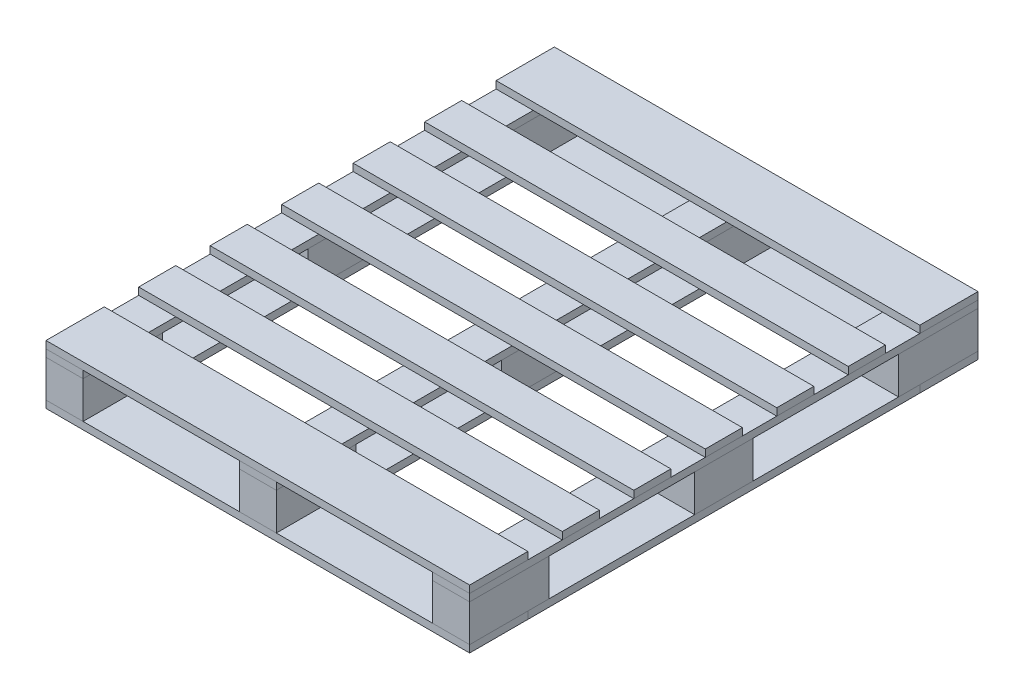
SolidWorks part; units mm, degrees
ref_plane "Front Plane" through (0, 0, 0) normal (0, 0, 1) x (1, 0, 0)
ref_plane "Top Plane" through (0, 0, 0) normal (0, 1, 0) x (1, 0, 0)
ref_plane "Right Plane" through (0, 0, 0) normal (1, 0, 0) x (0, 0, -1)
sketch "Sketch1" plane through (0, 0, 0) normal (0, 0, 1) x (1, 0, 0)
  line L0 (-508, 0) -> (508, 0) construction
  line L5 (-508, 70.612) -> (-508, -70.612) construction
  line L6 (508, 70.612) -> (508, -70.612) construction
  line L11 (-508, -70.612) -> (508, -70.612) construction
  line L12 (-508, 70.612) -> (508, 70.612) construction
  line L13 (-419.1, 70.612) -> (-419.1, -70.612) construction
  line L17 (0, 70.612) -> (0, -70.612) construction
  line L18 (-508, 0) -> (-419.1, 0)
  line L21 (419.1, 70.612) -> (419.1, -70.612) construction
  line L22 (-508, 53.1368) -> (508, 53.1368) construction
  line L23 (-508, -53.1368) -> (508, -53.1368) construction
  line L28 (-44.45, -70.612) -> (44.45, -70.612)
  line L29 (-44.45, -70.612) -> (-44.45, 70.612)
  line L30 (-44.45, 70.612) -> (44.45, 70.612)
  line L31 (44.45, -70.612) -> (44.45, 70.612)
  line L32 (-44.45, -70.612) -> (44.45, 70.612) construction
  line L33 (-44.45, 70.612) -> (44.45, -70.612) construction
  point P3 (0, 0)
  point P6 (-508, 0)
  point P9 (508, 0)
  point P23 (0, 0)
  point P32 (0, 0)
  dimension "D1" = 88.9
  dimension "Width" = 1016
  dimension "Height" = 141.224
  dimension "Maximum Fork Width" = 374.65
  dimension "D3" = 17.4752
  dimension "Maximum Fork Height" = 106.2736
sketch "Sketch2" plane through (0, 0, 0) normal (1, 0, 0) x (0, 0, -1)
  line L0 (609.6, 0) -> (-609.6, 0) construction
  point P4 (0, 0)
  dimension "Depth" = 1219.2
sketch "Sketch3" plane through (0, 0, 0) normal (0, 0, 1) x (1, 0, 0)
  line L34 (508, 53.1368) -> (508, 70.612) construction
  line L36 (-508, 70.612) -> (-508, -70.612) construction
  line L37 (-419.1, 70.612) -> (-419.1, -70.612) construction
  line L38 (-508, 35.6616) -> (-419.1, 35.6616)
  line L39 (-508, 35.6616) -> (-508, 53.1368)
  line L40 (-508, 53.1368) -> (-419.1, 53.1368)
  line L41 (-419.1, 35.6616) -> (-419.1, 53.1368)
  line L42 (-508, 53.1368) -> (508, 53.1368) construction
  line L43 (-44.45, -70.612) -> (-44.45, 70.612) construction
  line L44 (-44.45, 35.6616) -> (44.45, 35.6616)
  line L45 (-44.45, 35.6616) -> (-44.45, 53.1368)
  line L46 (-44.45, 53.1368) -> (44.45, 53.1368)
  line L47 (44.45, 35.6616) -> (44.45, 53.1368)
  line L48 (44.45, -70.612) -> (44.45, 70.612) construction
  line L50 (508, 53.1368) -> (419.1, 53.1368)
  line L51 (508, 53.1368) -> (508, 35.6616)
  line L52 (508, 35.6616) -> (419.1, 35.6616)
  line L53 (419.1, 53.1368) -> (419.1, 35.6616)
  line L54 (419.1, 70.612) -> (419.1, -70.612) construction
  line L55 (508, 70.612) -> (508, -70.612) construction
extrude "Boss-Extrude1" add sketch "Sketch3" along normal up to vertex (609.6 mm away) and the other way up to vertex (609.6 mm away) up to point (0, 0, 609.6) other way up to point (0, 0, -609.6)
sketch "Sketch4" plane through (0, 53.1368, 0) normal (0, -1, 0) x (-1, 0, 0)
  line L26 (508, 469.9) -> (-508, 469.9)
  line L27 (508, 469.9) -> (508, 609.6)
  line L28 (508, 609.6) -> (-508, 609.6)
  line L29 (-508, 469.9) -> (-508, 609.6)
  line L30 (0, -44.45) -> (0, -127) construction
  line L35 (508, 127) -> (-508, 127)
  line L36 (508, 127) -> (508, 215.9)
  line L37 (508, 215.9) -> (-508, 215.9)
  line L38 (-508, 127) -> (-508, 215.9)
  line L43 (508, 387.35) -> (-508, 387.35)
  line L44 (508, 387.35) -> (508, 298.45)
  line L45 (508, 298.45) -> (-508, 298.45)
  line L46 (-508, 387.35) -> (-508, 298.45)
  line L63 (508, 44.45) -> (-508, 44.45)
  line L64 (508, 44.45) -> (508, -44.45)
  line L65 (508, -609.6) -> (508, 609.6) construction
  line L66 (0, 44.45) -> (0, 127) construction
  line L67 (0, 215.9) -> (0, 298.45) construction
  line L68 (-508, -609.6) -> (-508, 609.6) construction
  line L69 (0, 609.6) -> (0, -609.6) construction
  line L70 (508, -44.45) -> (-508, -44.45)
  line L71 (-508, 44.45) -> (-508, -44.45)
  line L84 (508, -127) -> (-508, -127)
  line L85 (508, -127) -> (508, -215.9)
  line L86 (0, 387.35) -> (0, 469.9) construction
  line L87 (508, -215.9) -> (-508, -215.9)
  line L88 (-508, -127) -> (-508, -215.9)
  line L89 (508, -298.45) -> (-508, -298.45)
  line L90 (508, -298.45) -> (508, -387.35)
  line L91 (508, -387.35) -> (-508, -387.35)
  line L92 (-508, -298.45) -> (-508, -387.35)
  line L93 (508, -609.6) -> (-508, -609.6)
  line L94 (508, -609.6) -> (508, -469.9)
  line L95 (508, -469.9) -> (-508, -469.9)
  line L96 (-508, -609.6) -> (-508, -469.9)
  line L97 (0, -215.9) -> (0, -298.45) construction
  line L98 (0, -387.35) -> (0, -469.9) construction
  dimension "D1" = 139.7
  dimension "D3" = 88.9
extrude "Boss-Extrude2" add sketch "Sketch4" against normal up to vertex (17.4752 mm away) separate body up to point (-508, 70.612, 0)
sketch "Sketch9" plane through (0, 35.6616, 0) normal (0, -1, 0) x (1, 0, 0)
  line L0 (419.1, 609.6) -> (419.1, -609.6) construction
  line L1 (508, 609.6) -> (419.1, 609.6)
  line L2 (508, 609.6) -> (508, 419.1)
  line L3 (508, 419.1) -> (419.1, 419.1)
  line L4 (419.1, 609.6) -> (419.1, 419.1)
  line L5 (508, 609.6) -> (508, -609.6) construction
  line L6 (419.1, 69.85) -> (508, 69.85)
  line L7 (419.1, 69.85) -> (419.1, -69.85)
  line L8 (419.1, -69.85) -> (508, -69.85)
  line L9 (508, 69.85) -> (508, -69.85)
  line L10 (0, 0) -> (0, -609.6) construction
  line L11 (508, -609.6) -> (419.1, -609.6)
  line L12 (508, -609.6) -> (508, -419.1)
  line L13 (508, -419.1) -> (419.1, -419.1)
  line L14 (419.1, -609.6) -> (419.1, -419.1)
  line L15 (-44.45, -609.6) -> (44.45, -609.6) construction
  line L16 (44.45, 609.6) -> (-44.45, 609.6)
  line L17 (44.45, 609.6) -> (44.45, 419.1)
  line L18 (44.45, 419.1) -> (-44.45, 419.1)
  line L19 (-44.45, 609.6) -> (-44.45, 419.1)
  line L20 (-44.45, 69.85) -> (44.45, 69.85)
  line L21 (-44.45, 69.85) -> (-44.45, -69.85)
  line L22 (-44.45, -69.85) -> (44.45, -69.85)
  line L23 (44.45, 69.85) -> (44.45, -69.85)
  line L24 (44.45, -609.6) -> (-44.45, -609.6)
  line L25 (44.45, -609.6) -> (44.45, -419.1)
  line L26 (44.45, -419.1) -> (-44.45, -419.1)
  line L27 (-44.45, -609.6) -> (-44.45, -419.1)
  line L28 (-419.1, 609.6) -> (-508, 609.6)
  line L29 (-419.1, 609.6) -> (-419.1, 419.1)
  line L30 (-419.1, 419.1) -> (-508, 419.1)
  line L31 (-508, 609.6) -> (-508, 419.1)
  line L32 (-508, 69.85) -> (-419.1, 69.85)
  line L33 (-508, 69.85) -> (-508, -69.85)
  line L34 (-508, -69.85) -> (-419.1, -69.85)
  line L35 (-419.1, 69.85) -> (-419.1, -69.85)
  line L36 (-419.1, -609.6) -> (-508, -609.6)
  line L37 (-419.1, -609.6) -> (-419.1, -419.1)
  line L38 (-419.1, -419.1) -> (-508, -419.1)
  line L39 (-508, -609.6) -> (-508, -419.1)
  dimension "D1" = 190.5
  dimension "D2" = 139.7
  dimension "D3" = 349.25
  dimension "D4" = 3
extrude "Boss-Extrude4" add sketch "Sketch9" along normal up to vertex (88.7984 mm away) separate body up to point (-508, -53.1368, 0)
sketch "Sketch5" plane through (0, -53.1368, 0) normal (0, -1, 0) x (1, 0, 0)
  line L37 (-508, 609.6) -> (508, 609.6)
  line L38 (-508, 609.6) -> (-508, 469.9)
  line L39 (-508, 469.9) -> (508, 469.9)
  line L40 (508, 609.6) -> (508, 469.9)
  line L41 (-508, -609.6) -> (508, -609.6)
  line L42 (-508, -609.6) -> (-508, -469.9)
  line L43 (-508, -469.9) -> (508, -469.9)
  line L44 (508, -609.6) -> (508, -469.9)
extrude "Boss-Extrude3" add sketch "Sketch5" along normal up to vertex (17.4752 mm away) separate body up to point (-508, -70.612, 0)
sketch "Sketch11" plane through (0, -53.1368, 0) normal (0, -1, 0) x (1, 0, 0)
  line L0 (508, -469.9) -> (-508, -469.9) construction
  line L1 (-508, 469.9) -> (-419.1, 469.9)
  line L2 (-508, 469.9) -> (-508, -469.9)
  line L3 (-508, -469.9) -> (-419.1, -469.9)
  line L4 (-419.1, 469.9) -> (-419.1, -469.9)
  line L5 (-419.1, -609.6) -> (-419.1, -419.1) construction
  line L6 (-508, 469.9) -> (508, 469.9) construction
  line L7 (44.45, 469.9) -> (-44.45, 469.9)
  line L8 (44.45, 469.9) -> (44.45, -469.9)
  line L9 (44.45, -469.9) -> (-44.45, -469.9)
  line L10 (-44.45, 469.9) -> (-44.45, -469.9)
  line L11 (44.45, 419.1) -> (44.45, 609.6) construction
  line L12 (-44.45, -419.1) -> (-44.45, -609.6) construction
  line L13 (419.1, -419.1) -> (419.1, -609.6) construction
  line L14 (508, 469.9) -> (419.1, 469.9)
  line L15 (508, 469.9) -> (508, -469.9)
  line L16 (508, -469.9) -> (419.1, -469.9)
  line L17 (419.1, 469.9) -> (419.1, -469.9)
extrude "Boss-Extrude5" add sketch "Sketch11" along normal up to surface (17.4752 mm away) separate body up to face at (0, -70.612, 539.75)
sketch "Sketch7" plane through (0, 0, 0) normal (0, 1, 0) x (1, 0, 0)
  line L0 (0, 609.6) -> (508, 609.6) construction
  line L2 (508, 609.6) -> (508, 0) construction
  line L3 (508, 0) -> (508, 44.45) construction
  line L4 (508, 44.45) -> (0, 44.45) construction
  line L5 (-508, 44.45) -> (508, 44.45) construction
  line L6 (-508, 609.6) -> (0, 609.6) construction
